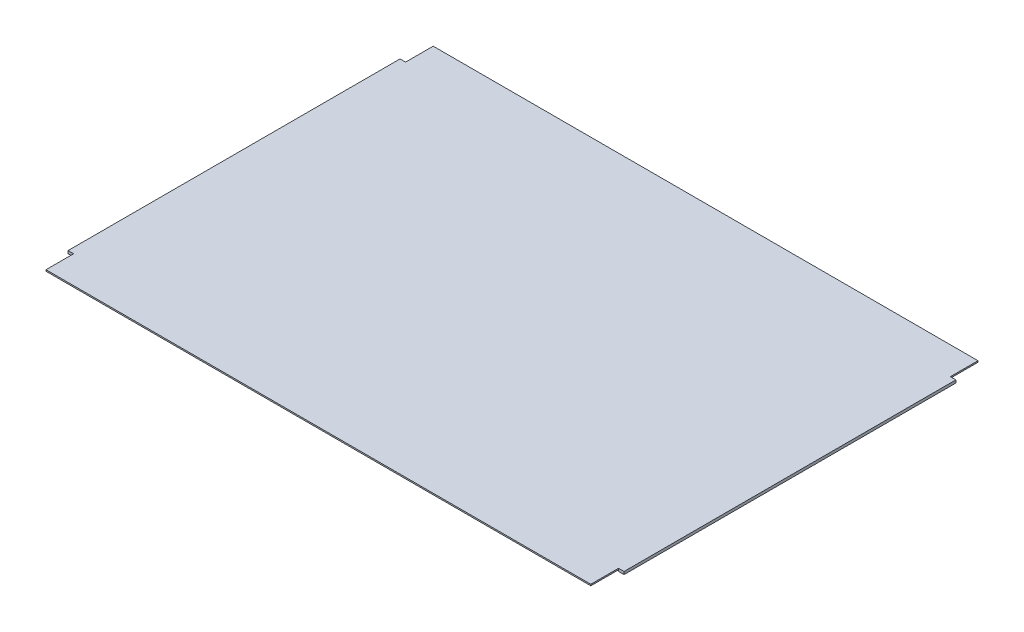
SolidWorks part; units mm, degrees
ref_plane "前视基准面" through (0, 0, 0) normal (0, 0, 1) x (1, 0, 0)
ref_plane "上视基准面" through (0, 0, 0) normal (0, 1, 0) x (1, 0, 0)
ref_plane "右视基准面" through (0, 0, 0) normal (1, 0, 0) x (0, 0, -1)
sketch "草图1" plane through (0, 0, 0) normal (0, 1, 0) x (1, 0, 0)
  line L8 (-98.5, 60) -> (-100.5, 60)
  line L14 (-98.5, 60) -> (-98.5, 70)
  line L23 (-98.5, 70) -> (98.5, 70)
  line L26 (-100.5, 60) -> (-100.5, -60)
  line L28 (-98.5, -70) -> (98.5, -70)
  line L29 (-98.5, -60) -> (-98.5, -70)
  line L30 (-98.5, -60) -> (-100.5, -60)
  line L31 (98.5, -60) -> (100.5, -60)
  line L32 (98.5, -60) -> (98.5, -70)
  line L33 (100.5, 60) -> (100.5, -60)
  line L34 (98.5, 60) -> (98.5, 70)
  line L35 (98.5, 60) -> (100.5, 60)
  point P5 (0, 0)
  point P7 (0, 0)
  point P14 (0, -70)
extrude "凸台-拉伸1" add sketch "草图1" along normal blind 1
sketch "草图4" plane through (0, 0, 0) normal (0, 1, 0) x (1, 0, 0)
  line L0 (98.5, -70) -> (98.5, -60) construction
  line L1 (-98.5, 70) -> (98.5, 70)
  line L2 (-98.5, 70) -> (-98.5, -70)
  line L3 (-98.5, -70) -> (98.5, -70)
  line L4 (98.5, 70) -> (98.5, -70)
extrude "切除-拉伸3" cut sketch "草图4" along normal blind 0.5
